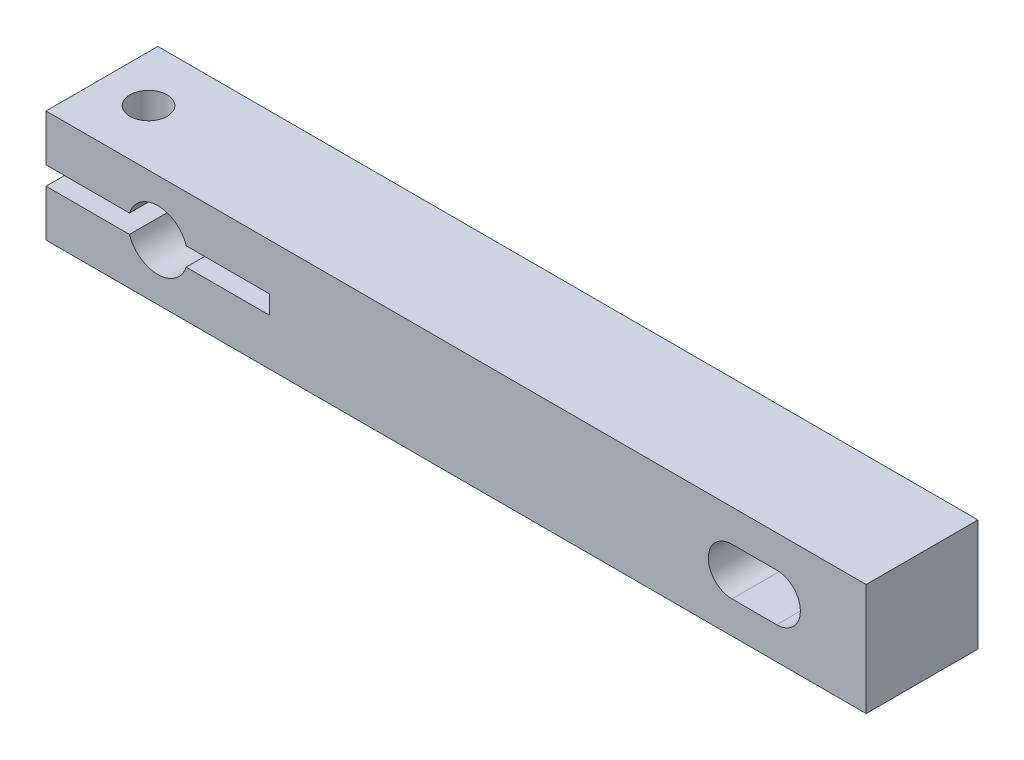
SolidWorks part; units mm, degrees
material "Fundición gris (SN)"
ref_plane "Alzado" through (0, 0, 0) normal (0, 0, 1) x (1, 0, 0)
ref_plane "Planta" through (0, 0, 0) normal (0, 1, 0) x (1, 0, 0)
ref_plane "Vista lateral" through (0, 0, 0) normal (1, 0, 0) x (0, 0, -1)
sketch "Croquis1" plane through (0, 0, 0) normal (1, 0, 0) x (0, 0, -1)
  line L1 (7.5, -7.5) -> (-7.5, -7.5)
  line L2 (7.5, -7.5) -> (7.5, 7.5)
  line L3 (7.5, 7.5) -> (-7.5, 7.5)
  line L4 (-7.5, -7.5) -> (-7.5, 7.5)
  line L5 (7.5, -7.5) -> (-7.5, 7.5) construction
  line L6 (7.5, 7.5) -> (-7.5, -7.5) construction
  point P0 (0, 0)
  dimension "D1" = 15
  dimension "D2" = 15
extrude "Saliente-Extruir1" add sketch "Croquis1" along normal mid plane 110
sketch "Croquis2" plane through (0, 0, 7.5) normal (0, 0, 1) x (1, 0, 0)
  line L0 (-55, 7.5) -> (-55, -7.5) construction
  line L2 (-25, -1.2399) -> (-55, -1.2399)
  line L3 (-25, -1.2399) -> (-25, 1.2399)
  line L4 (-25, 1.2399) -> (-55, 1.2399)
  line L5 (-55, -1.2399) -> (-55, 1.2399)
  line L6 (-25, -1.2399) -> (-55, 1.2399) construction
  line L7 (-25, 1.2399) -> (-55, -1.2399) construction
  circle A0 centre (-40, 0) radius 4
  line M1 (-55, 7.5) -> (-55, -7.5)
  dimension "D1" = 8
  dimension "D2" = 15
extrude "Cortar-Extruir1" cut sketch "Croquis2" against normal through all contours L2 A0 | L4 A0 L2 | L4 A0 | A0 L2 L3 L4 | A0 L4 L2 M1
sketch "Croquis3" plane through (0, 7.5, 0) normal (0, 1, 0) x (1, 0, 0)
  line L0 (-55, 7.5) -> (-55, -7.5) construction
  circle A0 centre (-48.75, 0) radius 2.5
  dimension "D1" = 5
  dimension "D2" = 6.25
extrude "Cortar-Extruir2" cut sketch "Croquis3" against normal through all
sketch "Croquis4" plane through (0, 0, 7.5) normal (0, 0, 1) x (1, 0, 0)
  line L0 (37, 0) -> (43, 0) construction
  line L1 (37, 3.175) -> (43, 3.175)
  line L2 (37, -3.175) -> (43, -3.175)
  line L3 (55, 7.5) -> (55, -7.5) construction
  arc A0 (37, 3.175) -> (37, -3.175) centre (37, 0) ccw
  arc A1 (43, -3.175) -> (43, 3.175) centre (43, 0) ccw
  point P2 (40, 0)
  dimension "D1" = 3.175
  dimension "D2" = 6
  dimension "D3" = 15
extrude "Cortar-Extruir3" cut sketch "Croquis4" against normal through all
